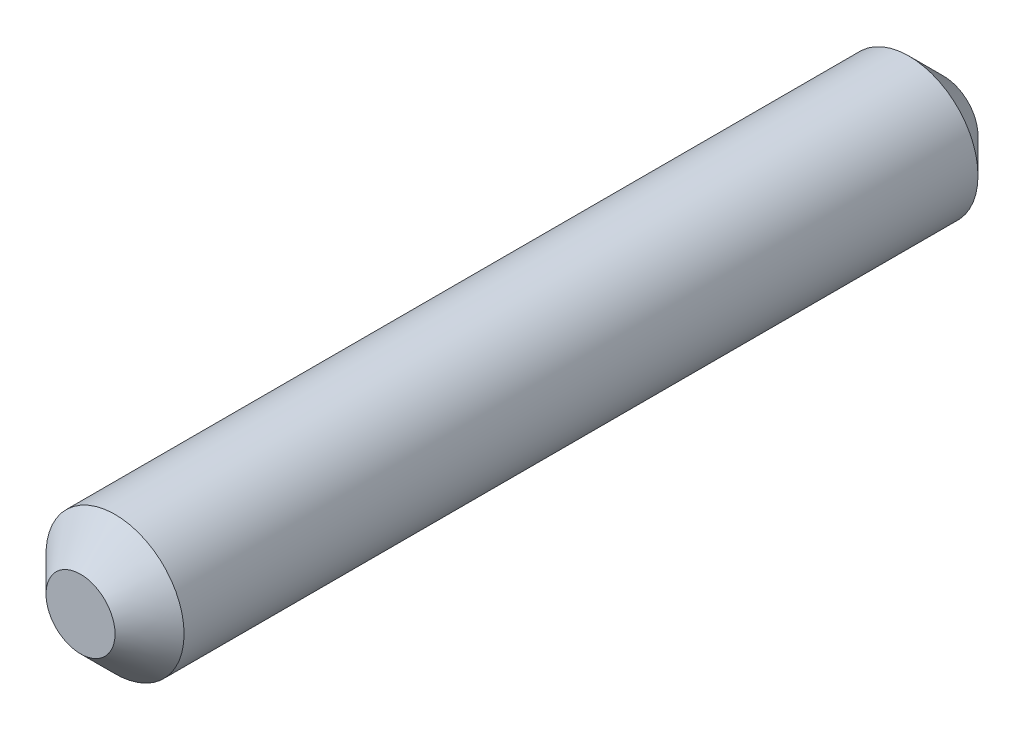
SolidWorks part; units mm, degrees
ref_plane "Front Plane" through (0, 0, 0) normal (0, 0, 1) x (1, 0, 0)
ref_plane "Top Plane" through (0, 0, 0) normal (0, 1, 0) x (1, 0, 0)
ref_plane "Right Plane" through (0, 0, 0) normal (1, 0, 0) x (0, 0, -1)
sketch "Sketch1" plane through (0, 0, 0) normal (0, 0, 1) x (1, 0, 0)
  circle A0 centre (0, 0) radius 2
  dimension "D1" = 4
extrude "Boss-Extrude1" add sketch "Sketch1" along normal blind 25
chamfer "Chamfer1" distance 1 angle 45 2 edges at (2, 0, 25) (2, 0, 0)
